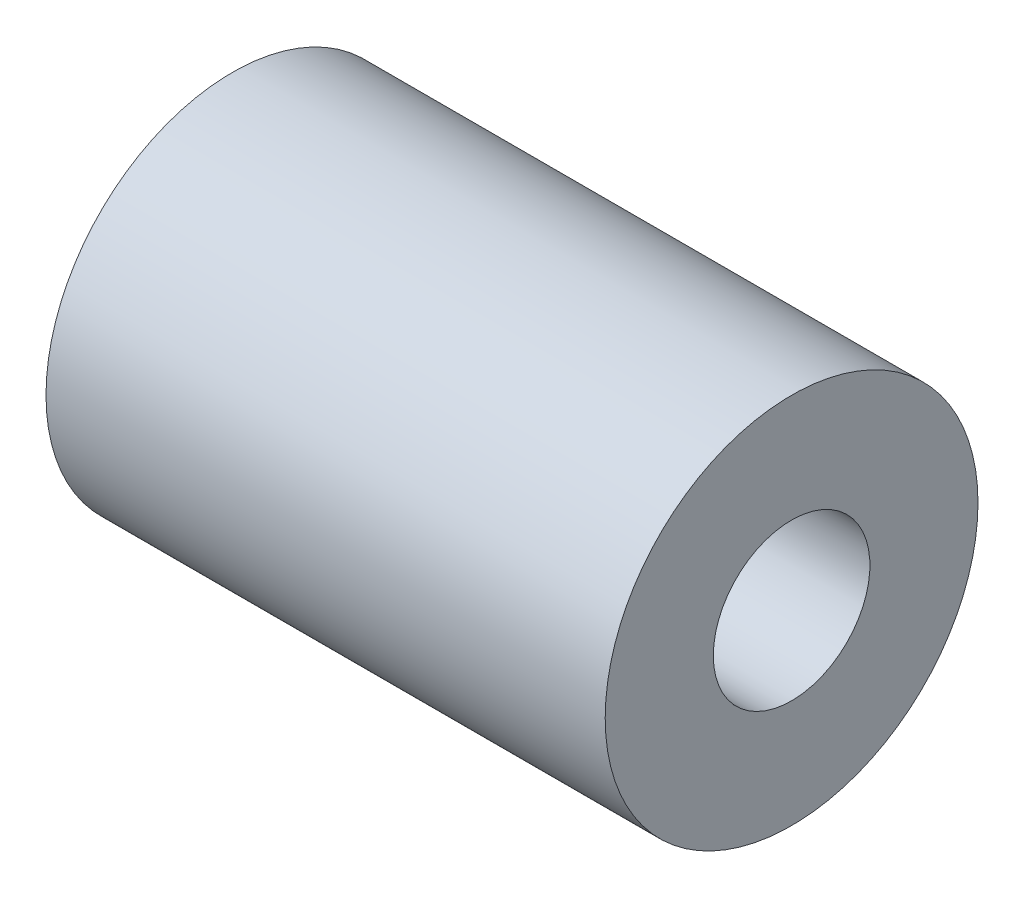
SolidWorks part; units mm, degrees
ref_plane "Front Plane" through (0, 0, 0) normal (0, 0, 1) x (1, 0, 0)
ref_plane "Top Plane" through (0, 0, 0) normal (0, 1, 0) x (1, 0, 0)
ref_plane "Right Plane" through (0, 0, 0) normal (1, 0, 0) x (0, 0, -1)
sketch "Sketch1" plane through (0, 0, 0) normal (1, 0, 0) x (0, 0, -1)
  circle A0 centre (0, 0) radius 25.4
  circle A1 centre (0, 0) radius 10.67
  dimension "D1" = 50.8
  dimension "D2" = 21.34
extrude "Boss-Extrude1" add sketch "Sketch1" along normal mid plane 76.2
